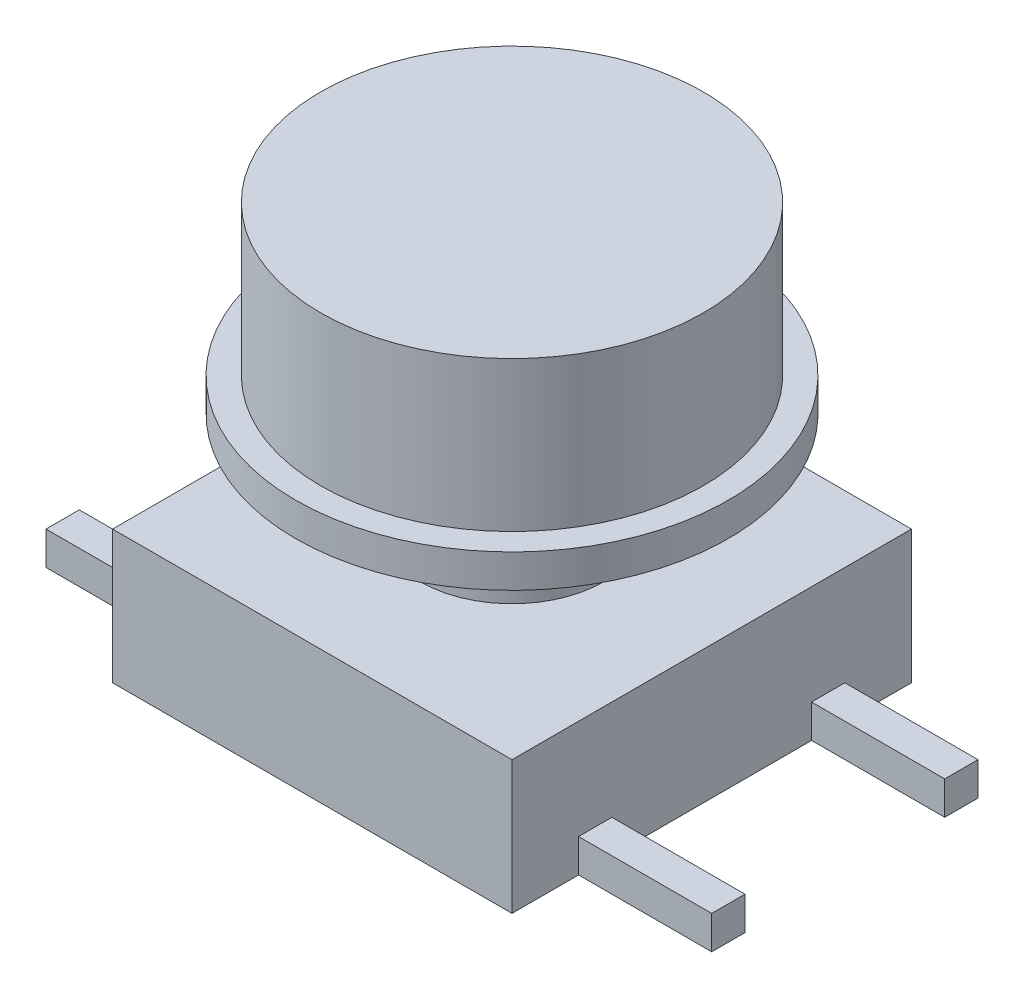
SolidWorks part; units mm, degrees
ref_plane "Front Plane" through (0, 0, 0) normal (0, 0, 1) x (1, 0, 0)
ref_plane "Top Plane" through (0, 0, 0) normal (0, 1, 0) x (1, 0, 0)
ref_plane "Right Plane" through (0, 0, 0) normal (1, 0, 0) x (0, 0, -1)
sketch "Sketch1" plane through (0, 0, 0) normal (0, 1, 0) x (1, 0, 0)
  line L1 (-6, -6) -> (6, -6)
  line L2 (-6, -6) -> (-6, 6)
  line L3 (-6, 6) -> (6, 6)
  line L4 (6, -6) -> (6, 6)
  line L5 (-6, -6) -> (6, 6) construction
  line L6 (-6, 6) -> (6, -6) construction
  point P0 (0, 0)
  dimension "D1" = 12
extrude "Boss-Extrude1" add sketch "Sketch1" along normal blind 4
sketch "Sketch2" plane through (0, 4, 0) normal (0, 1, 0) x (1, 0, 0)
  line L0 (0, 0) -> (0, 2.75) construction
  circle A0 centre (0, 0) radius 2.75
  dimension "D1" = 5.5
extrude "Boss-Extrude2" add sketch "Sketch2" along normal blind 3
sketch "Sketch3" plane through (0, 7, 0) normal (0, 1, 0) x (1, 0, 0)
  circle A0 centre (0, 0) radius 6.5
  dimension "D1" = 13
extrude "Boss-Extrude3" add sketch "Sketch3" along normal blind 1
sketch "Sketch4" plane through (0, 8, 0) normal (0, 1, 0) x (1, 0, 0)
  circle A0 centre (0, 0) radius 5.75
  dimension "D1" = 11.5
extrude "Boss-Extrude4" add sketch "Sketch4" along normal blind 5.5 from surface at -1 starting at face at (0, 7, 2.75)
sketch "Sketch5" plane through (6, 0, 0) normal (1, 0, 0) x (0, 0, -1)
  line L0 (-6, 0) -> (6, 0) construction
  line L1 (-4, 1) -> (-3, 1)
  line L2 (-4, 1) -> (-4, 0)
  line L3 (-4, 0) -> (-3, 0)
  line L4 (-3, 1) -> (-3, 0)
  line L5 (-4, 1) -> (-3, 0) construction
  line L6 (-4, 0) -> (-3, 1) construction
  line L7 (-6, 4) -> (-6, 0) construction
  point P0 (-3.5, 0.5)
  dimension "D1" = 2
  dimension "D2" = 1
  dimension "D3" = 1
extrude "Boss-Extrude5" add sketch "Sketch5" along normal blind 4
mirror "Mirror1" about plane through (0, 0, 0) normal (0, 0, 1) of "Boss-Extrude5"
mirror "Mirror2" about plane through (0, 0, 0) normal (1, 0, 0) of "Mirror1", "Boss-Extrude5"
